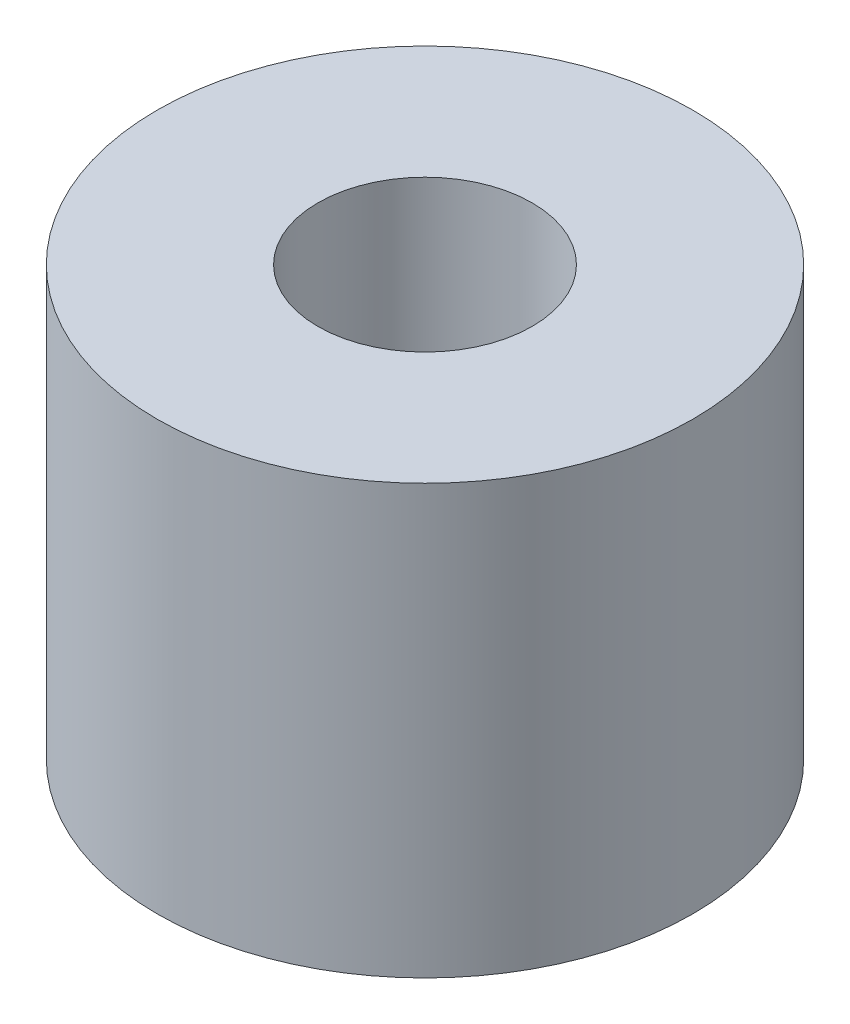
SolidWorks part; units mm, degrees
material "合金钢"
ref_plane "前视基准面" through (0, 0, 0) normal (0, 0, 1) x (1, 0, 0)
ref_plane "上视基准面" through (0, 0, 0) normal (0, 1, 0) x (1, 0, 0)
ref_plane "右视基准面" through (0, 0, 0) normal (1, 0, 0) x (0, 0, -1)
sketch "草图1" plane through (0, 0, 0) normal (0, 1, 0) x (1, 0, 0)
  circle A0 centre (0, 0) radius 2.5
  circle A1 centre (0, 0) radius 1
  dimension "D1" = 5
  dimension "D2" = 2
extrude "凸台-拉伸1" add sketch "草图1" along normal blind 4
